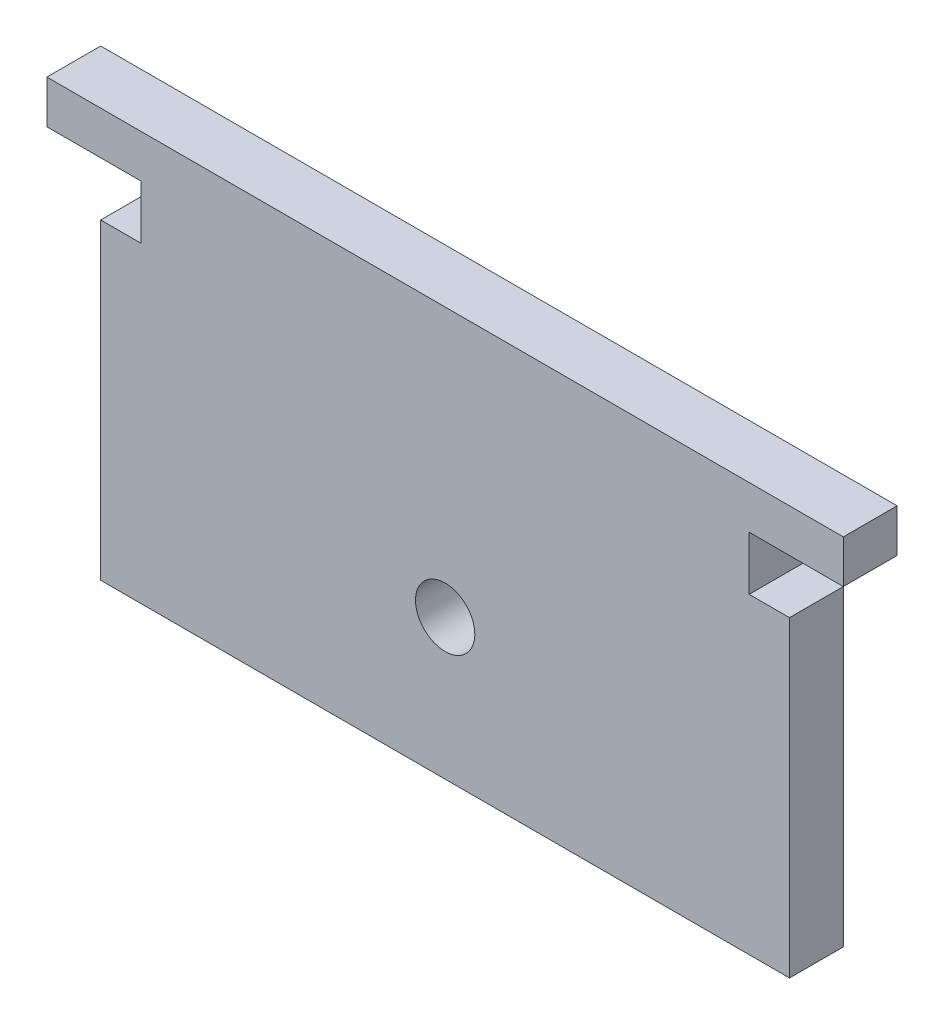
SolidWorks part; units mm, degrees
material "AISI 4130 Steel, annealed at 865C"
ref_plane "X-Y Datum" through (0, 0, 0) normal (0, 0, 1) x (1, 0, 0)
ref_plane "X-Z Datum" through (0, 0, 0) normal (0, 1, 0) x (1, 0, 0)
ref_plane "Y-Z Datum" through (0, 0, 0) normal (1, 0, 0) x (0, 0, -1)
sketch "Sketch1" plane through (0, 0, 0) normal (0, 0, 1) x (1, 0, 0)
  line L1 (-46.9951, -25.4) -> (46.9951, -25.4)
  line L2 (-46.9951, -25.4) -> (-46.9951, 25.4)
  line L3 (-46.9951, 25.4) -> (46.9951, 25.4)
  line L4 (46.9951, -25.4) -> (46.9951, 25.4)
  line L5 (-46.9951, -25.4) -> (46.9951, 25.4) construction
  line L6 (-46.9951, 25.4) -> (46.9951, -25.4) construction
  point P0 (0, 0)
  dimension "D1" = 93.9902
  dimension "D2" = 50.8
extrude "Boss-Extrude1" add sketch "Sketch1" along normal blind 6.35
sketch "Sketch2" plane through (0, 0, 6.35) normal (0, 0, 1) x (1, 0, 0)
  line L1 (-46.9951, -25.4) -> (-40.6451, -25.4)
  line L2 (-46.9951, -25.4) -> (-46.9951, 17.78)
  line L3 (-46.9951, 17.78) -> (-40.6451, 17.78)
  line L4 (-40.6451, -25.4) -> (-40.6451, 17.78)
  line L5 (46.9951, -25.4) -> (40.6451, -25.4)
  line L6 (46.9951, -25.4) -> (46.9951, 17.78)
  line L7 (46.9951, 17.78) -> (40.6451, 17.78)
  line L8 (40.6451, -25.4) -> (40.6451, 17.78)
  dimension "D1" = 6.35
  dimension "D2" = 43.18
  dimension "D3" = 6.35
extrude "Cut-Extrude1" cut sketch "Sketch2" against normal blind 6.35
sketch "Sketch3" plane through (0, 25.4, 0) normal (0, 1, 0) x (1, 0, 0)
  line L1 (-46.9951, 0) -> (46.9951, 0)
  line L2 (-46.9951, 0) -> (-46.9951, -6.35)
  line L3 (-46.9951, -6.35) -> (46.9951, -6.35)
  line L4 (46.9951, 0) -> (46.9951, -6.35)
extrude "Cut-Extrude2" cut sketch "Sketch3" against normal blind 2.54
sketch "Sketch5" plane through (-40.6451, 0, 0) normal (-1, 0, 0) x (0, 0, 1)
  line L0 (6.35, -25.4) -> (6.35, 17.78) construction
  line L1 (0, 17.78) -> (6.35, 17.78)
  line L2 (0, 17.78) -> (0, 11.43)
  line L3 (0, 11.43) -> (6.35, 11.43)
  line L4 (6.35, 17.78) -> (6.35, 11.43)
  dimension "D1" = 6.35
extrude "Cut-Extrude3" cut sketch "Sketch5" against normal blind 4.7625
mirror "Mirror1" about plane through (0, 0, 0) normal (1, 0, 0) of "Cut-Extrude3"
sketch "Sketch6" plane through (0, 0, 6.35) normal (0, 0, 1) x (1, 0, 0)
  line L12 (40.6451, 11.43) -> (35.8826, 11.43)
  line L13 (35.8826, 11.43) -> (35.8826, 17.78)
  line L14 (35.8826, 17.78) -> (46.9951, 17.78)
  line L15 (46.9951, 17.78) -> (46.9951, 22.86)
  line L16 (46.9951, 22.86) -> (-46.9951, 22.86)
  line L17 (-46.9951, 22.86) -> (-46.9951, 17.78)
  line L18 (-46.9951, 17.78) -> (-35.8826, 17.78)
  line L19 (-35.8826, 17.78) -> (-35.8826, 11.43)
  line L20 (-35.8826, 11.43) -> (-40.6451, 11.43)
  line L21 (-40.6451, 11.43) -> (-40.6451, -25.4)
  line L22 (-40.6451, -25.4) -> (40.6451, -25.4)
  line L23 (40.6451, -25.4) -> (40.6451, 11.43)
  line L24 (40.6451, 11.43) -> (35.8826, 11.43)
  line L25 (35.8826, 11.43) -> (35.8826, 17.78)
  line L26 (35.8826, 17.78) -> (46.9951, 17.78)
  line L27 (46.9951, 17.78) -> (46.9951, 22.86)
  line L28 (46.9951, 22.86) -> (-46.9951, 22.86)
  line L29 (-46.9951, 22.86) -> (-46.9951, 17.78)
  line L30 (-46.9951, 17.78) -> (-35.8826, 17.78)
  line L31 (-35.8826, 17.78) -> (-35.8826, 11.43)
  line L32 (-35.8826, 11.43) -> (-40.6451, 11.43)
  line L33 (-40.6451, 11.43) -> (-40.6451, -25.4)
  line L34 (-40.6451, -25.4) -> (40.6451, -25.4)
  line L35 (40.6451, -25.4) -> (40.6451, 11.43)
  circle A0 centre (0.0059, -8.8499) radius 3.5 construction
  circle A1 centre (0.0059, -8.8499) radius 3.5
  dimension "D1" = 0
extrude "Cut-Extrude4" cut sketch "Sketch6" against normal blind 6.35 contours A1
